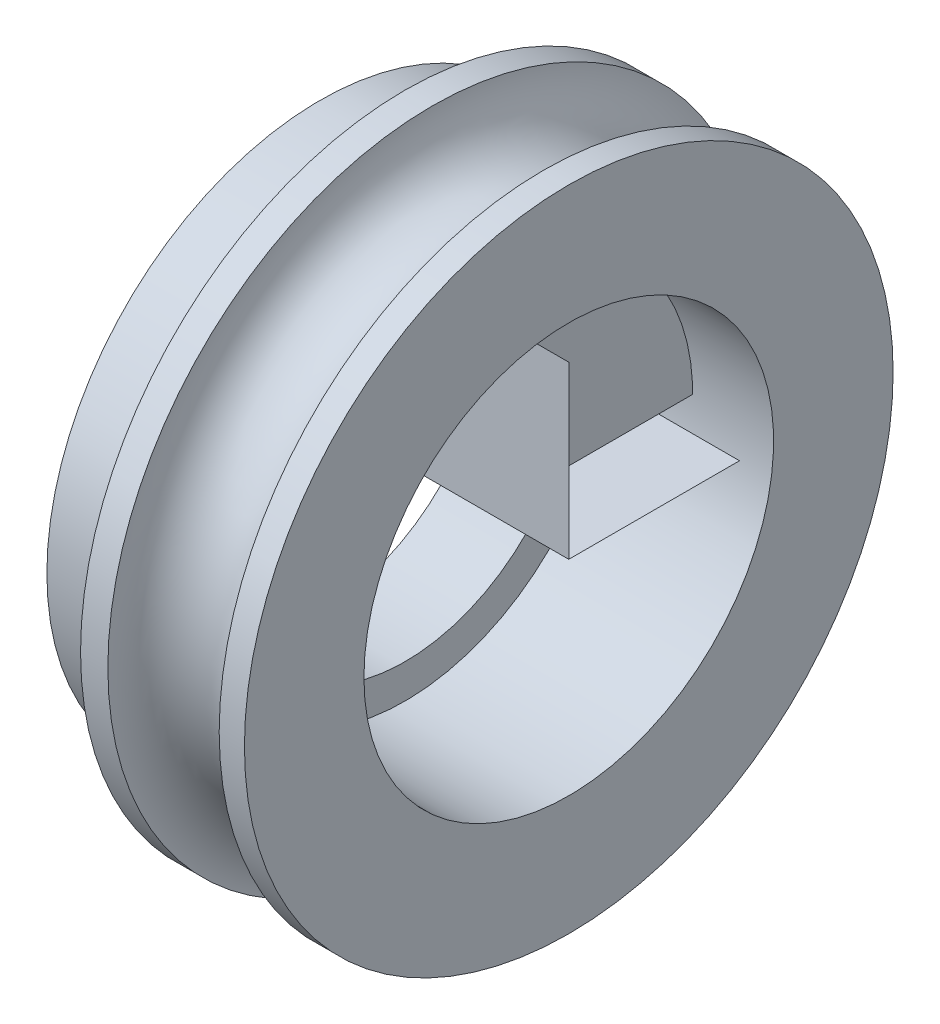
SolidWorks part; units mm, degrees
ref_plane "前视基准面" through (0, 0, 0) normal (0, 0, 1) x (1, 0, 0)
ref_plane "上视基准面" through (0, 0, 0) normal (0, 1, 0) x (1, 0, 0)
ref_plane "右视基准面" through (0, 0, 0) normal (1, 0, 0) x (0, 0, -1)
sketch "草图1" plane through (0, 0, 0) normal (0, 0, 1) x (1, 0, 0)
  line L0 (0, -9.5) -> (0.8, -9.5)
  line L1 (2.4301, -9.5) -> (2.4301, -7.8699) construction
  line L2 (-3.186, -5) -> (-3.186, -8)
  line L3 (0, -6) -> (4.8, -6)
  line L4 (-3.186, -8) -> (0, -8)
  line L5 (0, -5) -> (0, -6)
  line L6 (0, -8) -> (0, -9.5)
  line L7 (-3.186, -5) -> (0, -5)
  line L8 (-3.186, 0) -> (11.1867, 0) construction
  line L9 (4.0603, -9.5) -> (4.8, -9.5)
  line L11 (4.8, -9.5) -> (4.8, -6)
  arc A0 (4.0603, -9.5) -> (0.8, -9.5) centre (2.4301, -9.5) ccw
  dimension "D2" = 8
  dimension "D3" = 5
  dimension "D6" = 6
revolve "旋转1" add sketch "草图1" angle 360 about L8
sketch "草图2" plane through (-3.186, 0, 0) normal (-1, 0, 0) x (0, 0, 1)
  circle A0 centre (0, 0) radius 8.7129
extrude "切除-拉伸1" cut sketch "草图2" against normal blind 0.7
sketch "草图3" plane through (4.8, 0, 0) normal (1, 0, 0) x (0, 0, -1)
  line L0 (0, 0) -> (0, 5)
  line L1 (0, 0) -> (5, 0)
  circle A0 centre (0, 0) radius 5 construction
surface "曲面-拉伸1" sketch "草图3" parameters "D1"=5
sketch "草图4" plane through (0, 0, 0) normal (0, 1, 0) x (1, 0, 0)
  line L0 (0.8, 0) -> (4.0603, 0) construction
  line L1 (0.8, -9.5) -> (0.8, 9.5) construction
  line L2 (4.0603, -9.5) -> (4.0603, 9.5) construction
  line L3 (2.4301, 0) -> (2.4301, 6.2094)
surface "曲面-拉伸2" sketch "草图4" parameters "D1"=5
